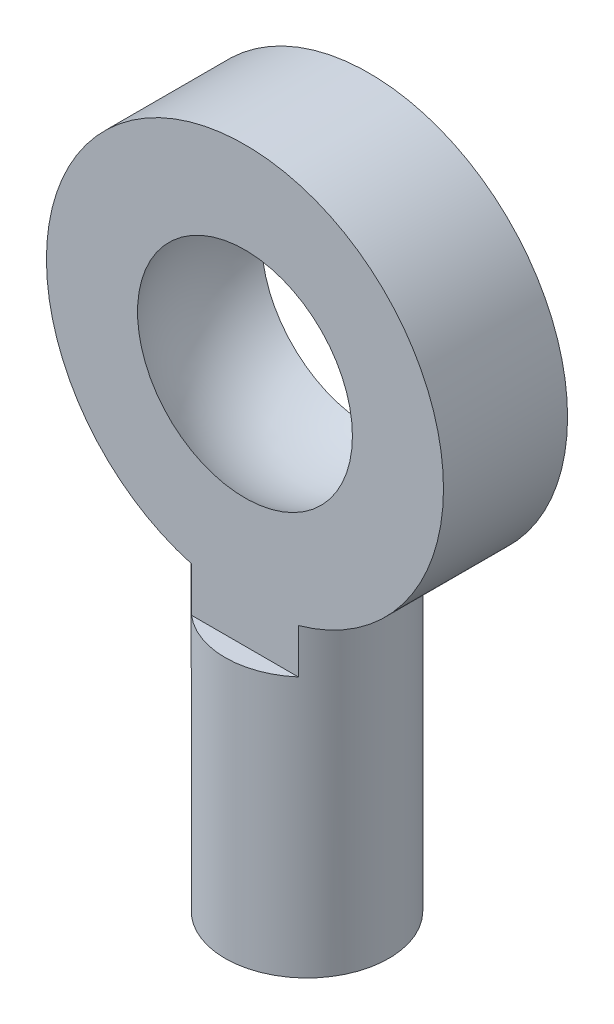
SolidWorks part; units mm, degrees
ref_plane "前视基准面" through (0, 0, 0) normal (0, 0, 1) x (1, 0, 0)
ref_plane "上视基准面" through (0, 0, 0) normal (0, 1, 0) x (1, 0, 0)
ref_plane "右视基准面" through (0, 0, 0) normal (1, 0, 0) x (0, 0, -1)
sketch "草图2" plane through (0, 0, 0) normal (0, 1, 0) x (1, 0, 0)
  circle A0 centre (0, 0) radius 1.65
  dimension "D1" = 3.3
extrude "凸台-拉伸1" add sketch "草图2" along normal blind 10
sketch "草图3" plane through (0, 0, 0) normal (0, 0, 1) x (1, 0, 0)
  line L0 (1.65, 10) -> (-1.65, 10) construction
  circle A0 centre (0, 10) radius 4
  dimension "D1" = 8
extrude "凸台-拉伸2" add sketch "草图3" along normal mid plane 2.5
sketch "草图5" plane through (0, 10, 0) normal (0, 1, 0) x (1, 0, 0)
  line L0 (1.077, -1.25) -> (-1.077, -1.25) construction
  line L1 (-1.077, 1.25) -> (1.077, 1.25) construction
  line L2 (1.077, -1.25) -> (-1.077, -1.25)
  line L3 (-1.077, 1.25) -> (1.077, 1.25)
  arc A0 (-1.077, -1.25) -> (1.077, -1.25) centre (0, 0) ccw construction
  arc A1 (1.077, 1.25) -> (-1.077, 1.25) centre (0, 0) ccw construction
  arc A2 (-1.077, -1.25) -> (1.077, -1.25) centre (0, 0) ccw
  arc A3 (1.077, 1.25) -> (-1.077, 1.25) centre (0, 0) ccw
extrude "切除-拉伸1" cut sketch "草图5" against normal mid plane 5
sketch "草图6" plane through (0, 7.5, 0) normal (0, 1, 0) x (1, 0, 0)
  line L7 (-1.077, 1.25) -> (1.077, 1.25)
  line L8 (-1.077, 1.25) -> (1.077, 1.25)
  line L9 (1.077, -1.25) -> (-1.077, -1.25)
  line L10 (1.077, -1.25) -> (-1.077, -1.25)
  arc A7 (1.077, 1.25) -> (-1.077, 1.25) centre (0, 0) ccw
  arc A8 (1.077, 1.25) -> (-1.077, 1.25) centre (0, 0) ccw
  arc A9 (-1.077, -1.25) -> (1.077, -1.25) centre (0, 0) ccw
  arc A10 (-1.077, -1.25) -> (1.077, -1.25) centre (0, 0) ccw
  dimension "D1" = 0
  dimension "D2" = 0
extrude "切除-拉伸2" cut sketch "草图6" against normal mid plane 4.5
sketch "草图7" plane through (0, 0, 1.25) normal (0, 0, 1) x (1, 0, 0)
  circle A0 centre (0, 10) radius 2
  dimension "D1" = 4
sketch "草图8" plane through (0, 0, 0) normal (0, -1, 0) x (1, 0, 0)
  circle A0 centre (0, 0) radius 1.1
  dimension "D1" = 2.2
extrude "切除-拉伸4" cut sketch "草图8" against normal blind 5
sketch "草图9" plane through (0, 0, 0) normal (0, 0, 1) x (1, 0, 0)
  line L0 (0, 12.5) -> (0, 7.5)
  arc A0 (0, 7.5) -> (0, 12.5) centre (0, 10) ccw
  dimension "D1" = 5
extrude "切除-拉伸5" cut sketch "草图7" against normal blind 10 contours A0
revolve "切除-旋转2" cut sketch "草图9" angle 360 about L0
